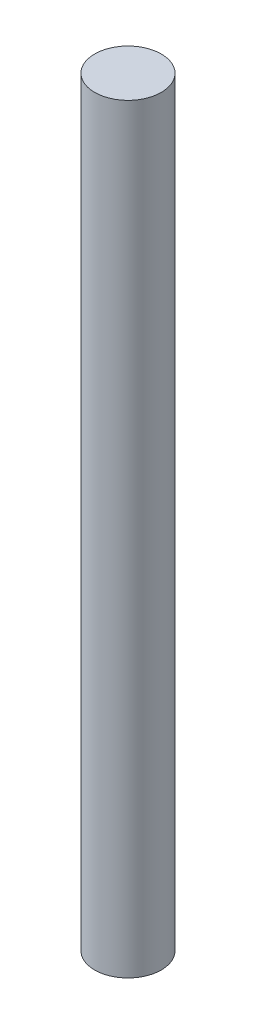
SolidWorks part; units mm, degrees
ref_plane "Front Plane" through (0, 0, 0) normal (0, 0, 1) x (1, 0, 0)
ref_plane "Top Plane" through (0, 0, 0) normal (0, 1, 0) x (1, 0, 0)
ref_plane "Right Plane" through (0, 0, 0) normal (1, 0, 0) x (0, 0, -1)
sketch "Sketch1" plane through (0, 0, 0) normal (0, 1, 0) x (1, 0, 0)
  circle A0 centre (0, 0) radius 3.78
  dimension "D1" = 7.56
extrude "Boss-Extrude1" add sketch "Sketch1" along normal blind 86.3
